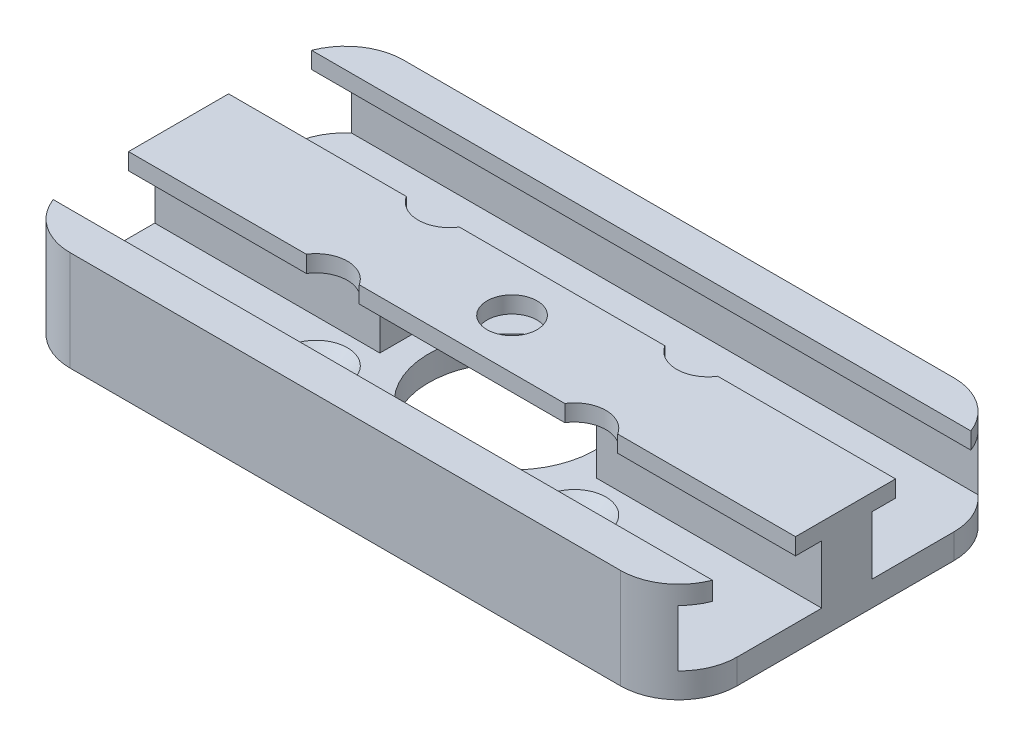
SolidWorks part; units mm, degrees
ref_plane "Front Plane" through (0, 0, 0) normal (0, 0, 1) x (1, 0, 0)
ref_plane "Top Plane" through (0, 0, 0) normal (0, 1, 0) x (1, 0, 0)
ref_plane "Right Plane" through (0, 0, 0) normal (1, 0, 0) x (0, 0, -1)
sketch "Sketch1" plane through (0, 0, 0) normal (0, 1, 0) x (1, 0, 0)
  line L1 (40, 20) -> (-40, 20)
  line L2 (40, 20) -> (40, -20)
  line L3 (40, -20) -> (-40, -20)
  line L4 (-40, 20) -> (-40, -20)
  line L5 (40, 20) -> (-40, -20) construction
  line L6 (40, -20) -> (-40, 20) construction
  circle A0 centre (0, 0) radius 10
  point P0 (0, 0)
  dimension "D1" = 80
  dimension "D2" = 40
extrude "Boss-Extrude1" add sketch "Sketch1" along normal blind 3
sketch "Sketch2" plane through (0, 3, 0) normal (0, 1, 0) x (1, 0, 0)
  line L1 (40, -20) -> (40, 20) construction
  line L2 (-40, 20) -> (40, 20)
  line L3 (-40, 20) -> (-40, 15.5)
  line L4 (-40, 15.5) -> (40, 15.5)
  line L5 (40, 20) -> (40, 15.5)
  line L7 (-40, -20) -> (40, -20)
  line L8 (-40, -20) -> (-40, -15.5)
  line L9 (-40, -15.5) -> (40, -15.5)
  line L10 (40, -20) -> (40, -15.5)
  point P12 (0, 0)
  dimension "D1" = 4.5
  dimension "D2" = 4.5
extrude "Boss-Extrude2" add sketch "Sketch2" along normal blind 9
sketch "Sketch3" plane through (-40, 0, 0) normal (-1, 0, 0) x (0, 0, 1)
  line L1 (-15.5, 3) -> (-18.3, 3)
  line L2 (-15.5, 3) -> (-15.5, 10)
  line L3 (-15.5, 10) -> (-18.3, 10)
  line L4 (-18.3, 3) -> (-18.3, 10)
  line L5 (15.5, 3) -> (18, 3)
  line L6 (15.5, 3) -> (15.5, 9.8)
  line L7 (15.5, 9.8) -> (18, 9.8)
  line L8 (18, 3) -> (18, 9.8)
  dimension "D1" = 2.8
  dimension "D2" = 7
  dimension "D3" = 2.5
  dimension "D4" = 6.8
extrude "Cut-Extrude1" cut sketch "Sketch3" against normal blind 80
sketch "Sketch4" plane through (0, 3, 0) normal (0, 1, 0) x (1, 0, 0)
  line L0 (40, 20) -> (-40, 20) construction
  line L1 (40, -18) -> (40, 18.3) construction
  line L2 (-40, 18.3) -> (-40, -18) construction
  line L3 (-40, -20) -> (40, -20) construction
  circle A0 centre (-15.5, 8) radius 3.75
  circle A1 centre (-15.5, -8) radius 3.75
  circle A3 centre (15.5, -8) radius 3.75
  circle A4 centre (15.5, 8) radius 3.75
  dimension "D1" = 7.5
  dimension "D2" = 7.5
  dimension "D3" = 16
  dimension "D4" = 31
  dimension "D5" = 12
  dimension "D6" = 12
  dimension "D7" = 31
  dimension "D8" = 16
  dimension "D9" = 12
  dimension "D10" = 12
  dimension "D11" = 24.5
  dimension "D12" = 24.5
  dimension "D13" = 15.5
sketch "Sketch5" plane through (0, 0, 0) normal (0, -1, 0) x (1, 0, 0)
  circle A0 centre (-15.5, 8) radius 1.75
  circle A1 centre (-15.5, -8) radius 1.75
  circle A2 centre (15.5, 8) radius 1.75
  circle A3 centre (15.5, -8) radius 1.75
extrude "Cut-Extrude3" cut sketch "Sketch5" against normal blind 1
extrude "Cut-Extrude4" cut sketch "Sketch4" against normal blind 2 draft 45
fillet "Fillet1" radius 7 4 edges at (40, 6, 20) (40, 6, -20) (-40, 6, 20) (-40, 6, -20)
sketch "Sketch6" plane through (0, 3, 0) normal (0, 1, 0) x (1, 0, 0)
  line L0 (-40, 3.1453) -> (-40, -2.8547)
  line L1 (-40, 13) -> (-40, -13) construction
  line L2 (-40, -2.8547) -> (-13, -2.8547)
  line L3 (-13, -2.8547) -> (-13, 3.1453)
  line L4 (-13, 3.1453) -> (-40, 3.1453)
  line L5 (0, 0) -> (-40, 0.1453) construction
  line L6 (0, 0) -> (0, -10) construction
  line L7 (13, -2.8547) -> (13, 3.1453)
  line L8 (40, -2.8547) -> (13, -2.8547)
  line L9 (40, 3.1453) -> (40, -2.8547)
  line L10 (13, 3.1453) -> (40, 3.1453)
  circle A0 centre (0, 0) radius 10 construction
  dimension "D1" = 6
  dimension "D2" = 27
  dimension "D3" = 3
extrude "Boss-Extrude3" add sketch "Sketch6" along normal blind 7
sketch "Sketch7" plane through (0, 10, 0) normal (0, 1, 0) x (1, 0, 0)
  line L0 (-40, -2.8547) -> (-40, -13) construction
  line L1 (40, 6) -> (18.6721, 6)
  line L2 (40, 6) -> (40, -6)
  line L3 (40, -6) -> (18.6721, -6)
  line L4 (-40, 6) -> (-40, -6)
  line L7 (-40, 0) -> (40, 0) construction
  line L8 (0, 6) -> (0, -6) construction
  line L9 (-18.6721, 6) -> (-40, 6)
  line L10 (-18.6721, -6) -> (-40, -6)
  line L11 (12.3279, -6) -> (-12.3279, -6)
  line L12 (12.3279, 6) -> (-12.3279, 6)
  arc A0 (-18.6721, 6) -> (-12.3279, 6) centre (-15.5, 8) ccw
  arc A1 (-18.6721, -6) -> (-12.3279, -6) centre (-15.5, -8) cw
  arc A2 (18.6721, -6) -> (12.3279, -6) centre (15.5, -8) ccw
  arc A3 (18.6721, 6) -> (12.3279, 6) centre (15.5, 8) cw
  circle A4 centre (0, 0) radius 3
  point P0 (0, 0)
  dimension "D1" = 12
extrude "Boss-Extrude4" add sketch "Sketch7" along normal blind 2
equation "\"D3@Cut-Extrude4\"=arccotan( 45)"
